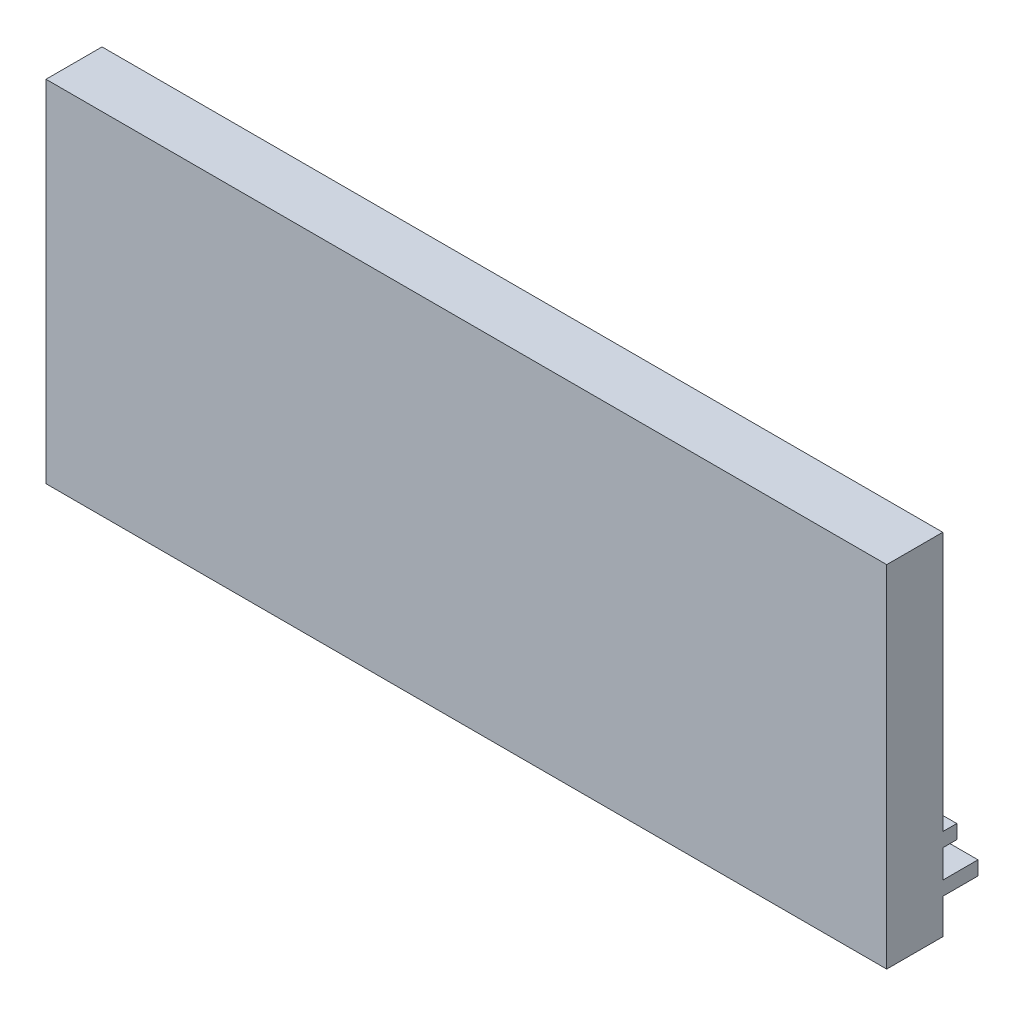
SolidWorks part; units mm, degrees
ref_plane "Front Plane" through (0, 0, 0) normal (0, 0, 1) x (1, 0, 0)
ref_plane "Top Plane" through (0, 0, 0) normal (0, 1, 0) x (1, 0, 0)
ref_plane "Right Plane" through (0, 0, 0) normal (1, 0, 0) x (0, 0, -1)
sketch "Sketch1" plane through (0, 0, 0) normal (0, 0, 1) x (1, 0, 0)
  line L1 (-25.5838, 14.7208) -> (34.4162, 14.7208)
  line L2 (-25.5838, 14.7208) -> (-25.5838, -10.2792)
  line L3 (-25.5838, -10.2792) -> (34.4162, -10.2792)
  line L4 (34.4162, 14.7208) -> (34.4162, -10.2792)
  dimension "D1" = 60
  dimension "D2" = 25
extrude "Boss-Extrude1" add sketch "Sketch1" along normal blind 4
sketch "Sketch2" plane through (0, 0, 0) normal (0, 0, -1) x (-1, 0, 0)
  line L0 (25.5838, 14.7208) -> (25.5838, -10.2792) construction
  line L1 (5.5838, -6.7792) -> (-34.4162, -6.7792)
  line L2 (5.5838, -6.7792) -> (5.5838, -7.7792)
  line L3 (5.5838, -7.7792) -> (-34.4162, -7.7792)
  line L4 (-34.4162, -6.7792) -> (-34.4162, -7.7792)
  line L5 (25.5838, -10.2792) -> (-34.4162, -10.2792) construction
  point P4 (5.5838, -7.2792)
  dimension "D1" = 40
  dimension "D2" = 1
  dimension "D3" = 20
  dimension "D4" = 2.5
extrude "Boss-Extrude2" add sketch "Sketch2" along normal blind 2.5146
sketch "Sketch3" plane through (0, 0, 0) normal (0, 0, -1) x (-1, 0, 0)
  line L0 (25.5838, 14.7208) -> (25.5838, -10.2792) construction
  line L1 (-34.4162, -3.7792) -> (5.5838, -3.7792)
  line L2 (-34.4162, -3.7792) -> (-34.4162, -4.7792)
  line L3 (-34.4162, -4.7792) -> (5.5838, -4.7792)
  line L4 (5.5838, -3.7792) -> (5.5838, -4.7792)
  line L5 (5.5838, -6.7792) -> (-34.4162, -6.7792) construction
  dimension "D1" = 40
  dimension "D2" = 20
  dimension "D3" = 1
  dimension "D4" = 2
extrude "Boss-Extrude3" add sketch "Sketch3" along normal blind 1
